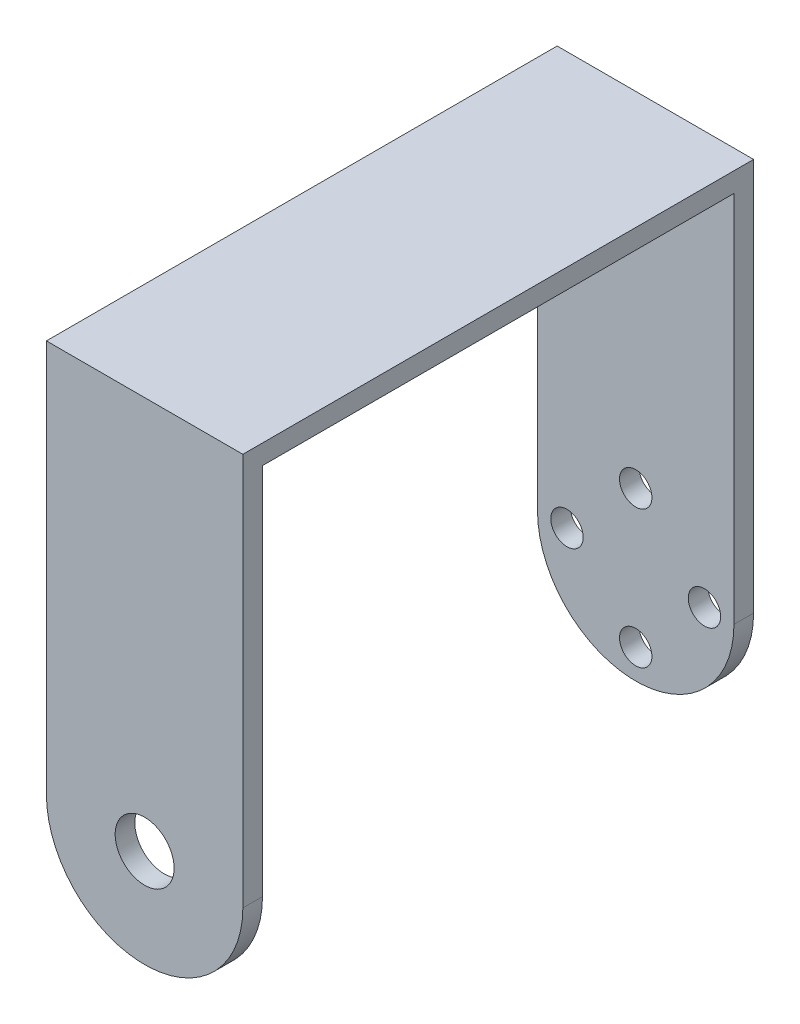
SolidWorks part; units mm, degrees
ref_plane "前视基准面" through (0, 0, 0) normal (0, 0, 1) x (1, 0, 0)
ref_plane "上视基准面" through (0, 0, 0) normal (0, 1, 0) x (1, 0, 0)
ref_plane "右视基准面" through (0, 0, 0) normal (1, 0, 0) x (0, 0, -1)
sketch "草图1" plane through (0, 0, 0) normal (0, 0, 1) x (1, 0, 0)
  line L2 (0, 0) -> (0, 40)
  line L3 (0, 40) -> (20, 40)
  line L4 (20, 0) -> (20, 40)
  arc A0 (20, 0) -> (0, 0) centre (10, 0) cw
  dimension "D1" = 20
  dimension "D2" = 40
extrude "凸台-拉伸1" add sketch "草图1" along normal blind 2
sketch "草图2" plane through (0, 0, 2) normal (0, 0, 1) x (1, 0, 0)
  line L0 (20, 0) -> (20, 40) construction
  line L1 (0, 40) -> (20, 40)
  line L2 (0, 40) -> (0, 38)
  line L3 (0, 38) -> (20, 38)
  line L4 (20, 40) -> (20, 38)
  dimension "D1" = 2
extrude "凸台-拉伸2" add sketch "草图2" along normal blind 50
sketch "草图3" plane through (0, 40, 0) normal (0, 1, 0) x (1, 0, 0)
  line L0 (0, -26) -> (20, -26) construction
  line L1 (0, -52) -> (0, 0) construction
  line L2 (20, -52) -> (20, 0) construction
ref_plane "基准面1" through (0, 0, 26) normal (0, 0, 1) x (1, 0, 0)
mirror "镜向1" about plane through (0, 0, 26) normal (0, 0, 1) of "凸台-拉伸1"
sketch "草图4" plane through (0, 0, 52) normal (0, 0, 1) x (1, 0, 0)
  line L0 (20, 0) -> (0, 0) construction
  circle A0 centre (10, 0) radius 3
  dimension "D1" = 6
  dimension "D2" = 10
extrude "切除-拉伸1" cut sketch "草图4" against normal up to next
sketch "草图5" plane through (0, 0, 0) normal (0, 0, -1) x (-1, 0, 0)
  line L0 (0, 0) -> (-20, 0) construction
  line L1 (-10, 0) -> (-10, -10) construction
  arc A0 (-20, 0) -> (0, 0) centre (-10, 0) ccw construction
  circle A1 centre (-10, -7) radius 1.65
  circle A2 centre (-17, 0) radius 1.65
  circle A3 centre (-10, 7) radius 1.65
  circle A4 centre (-3, 0) radius 1.65
  point P20 (-10, 0)
  dimension "D1" = 3.3
  dimension "D2" = 7
  dimension "D3" = 4
extrude "切除-拉伸2" cut sketch "草图5" against normal up to next
